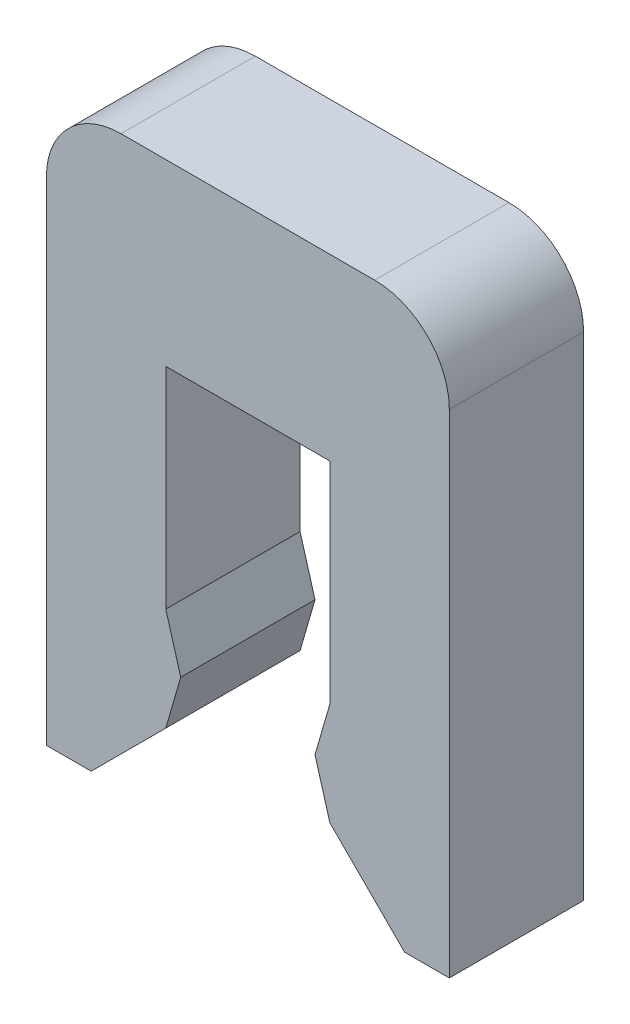
SolidWorks part; units mm, degrees
ref_plane "Спереди" through (0, 0, 0) normal (0, 0, 1) x (1, 0, 0)
ref_plane "Сверху" through (0, 0, 0) normal (0, 1, 0) x (1, 0, 0)
ref_plane "Справа" through (0, 0, 0) normal (1, 0, 0) x (0, 0, -1)
sketch "Эскиз1" plane through (0, 0, 0) normal (0, 0, 1) x (1, 0, 0)
  line L0 (-0.55, 0) -> (0.55, 0)
  line L1 (0.55, 0) -> (0.55, -2.6)
  line L2 (0.55, -2.6) -> (1.35, -2.6)
  line L3 (1.35, -2.6) -> (1.35, 1.2)
  line L4 (1.35, 1.2) -> (-1.35, 1.2)
  line L5 (0, 1.2) -> (0, 0) construction
  line L6 (-0.55, 0) -> (-0.55, -2.6)
  line L7 (-0.55, -2.6) -> (-1.35, -2.6)
  line L8 (-1.35, -2.6) -> (-1.35, 1.2)
  dimension "D1" = 0.55
  dimension "D2" = 0.8
  dimension "D4" = 2.6
  dimension "D5" = 3.8
extrude "Бобышка-Вытянуть1" add sketch "Эскиз1" along normal blind 0.9
chamfer "Фаска1" distance 0.5 angle 45 2 edges at (-0.55, -2.6, 0.45) (0.55, -2.6, 0.45)
fillet "Скругление1" radius 0.5 2 edges at (1.35, 1.2, 0.45) (-1.35, 1.2, 0.45)
sketch "Эскиз2" plane through (0, 0, 0.9) normal (0, 0, 1) x (1, 0, 0)
  line L0 (-0.55, -2.1) -> (-0.55, -1.409)
  line L1 (-0.55, -2.1) -> (-0.55, 0) construction
  line L2 (-0.55, -1.409) -> (-0.45, -1.7545)
  line L3 (-0.45, -1.7545) -> (-0.55, -2.1)
  line L4 (-0.45, -1.7545) -> (-0.55, -1.7545) construction
  dimension "D1" = 0.1
extrude "Бобышка-Вытянуть2" add sketch "Эскиз2" against normal blind 0.9
mirror "Зеркальное отражение1" about plane through (0, 0, 0) normal (1, 0, 0) of "Бобышка-Вытянуть2"
